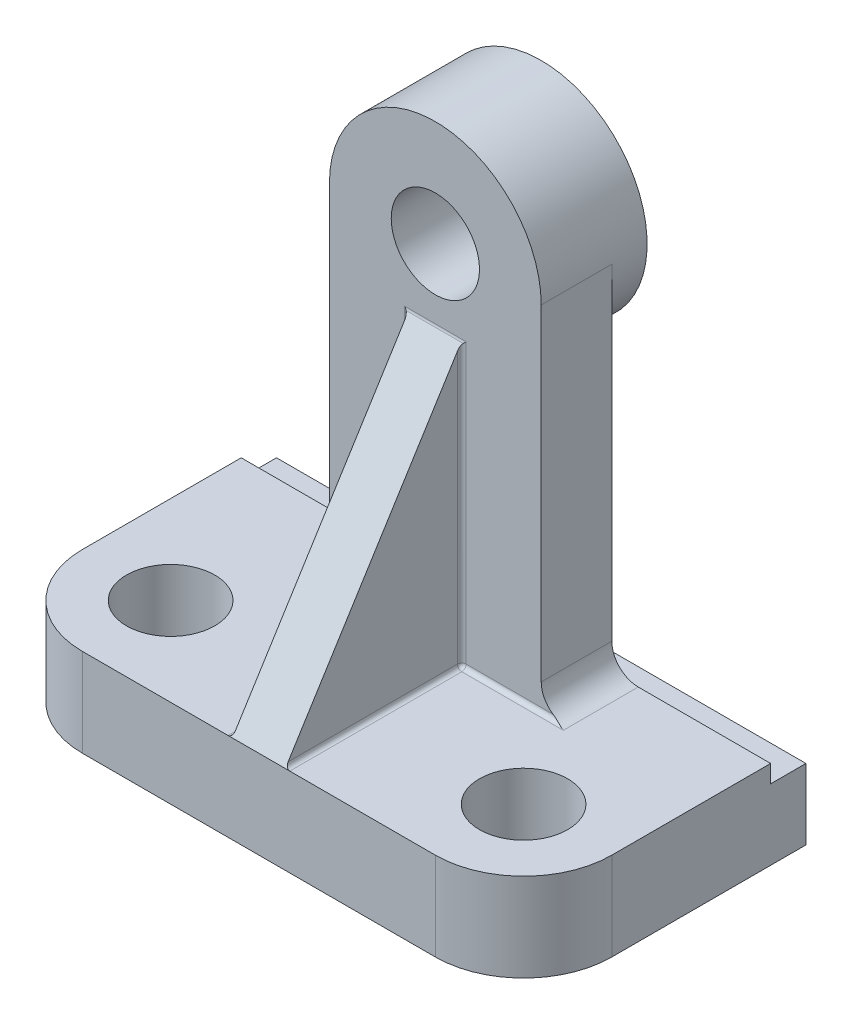
SolidWorks part; units mm, degrees
ref_plane "Front Plane" through (0, 0, 0) normal (0, 0, 1) x (1, 0, 0)
ref_plane "Top Plane" through (0, 0, 0) normal (0, 1, 0) x (1, 0, 0)
ref_plane "Right Plane" through (0, 0, 0) normal (1, 0, 0) x (0, 0, -1)
sketch "Sketch2" plane through (0, 0, 0) normal (0, 1, 0) x (1, 0, 0)
  line L0 (-64.7082, 0) -> (15.2918, 0)
  line L1 (35.2918, 20) -> (35.2918, 64)
  line L4 (35.2918, 20) -> (-131.6865, 20) construction
  line L5 (-84.7082, 20) -> (-84.7082, 64)
  line L6 (-84.7082, 64) -> (35.2918, 64)
  arc A0 (15.2918, 0) -> (35.2918, 20) centre (15.2918, 20) ccw
  arc A2 (-64.7082, 0) -> (-84.7082, 20) centre (-64.7082, 20) cw
  circle A3 centre (-64.7082, 20) radius 10
  circle A4 centre (15.2918, 20) radius 10
  dimension "D1" = 20
  dimension "D2" = 20
  dimension "D5" = 20
  dimension "D6" = 20
  dimension "D3" = 80
  dimension "D4" = 64
extrude "Boss-Extrude1" add sketch "Sketch2" along normal blind 20
sketch "Sketch3" plane through (0, 20, 0) normal (0, 1, 0) x (1, 0, 0)
  line L0 (35.2918, 20) -> (35.2918, 64) construction
  line L1 (-84.7082, 64) -> (35.2918, 64)
  line L2 (-84.7082, 64) -> (-84.7082, 56)
  line L3 (-84.7082, 56) -> (35.2918, 56)
  line L4 (35.2918, 64) -> (35.2918, 56)
  dimension "D1" = 8
extrude "Cut-Extrude1" cut sketch "Sketch3" against normal blind 4
ref_plane "Plane2" through (0, 0, -56) normal (0, 0, -1) x (-1, 0, 0)
sketch "Sketch7" plane through (0, 0, -56) normal (0, 0, -1) x (-1, 0, 0)
  line L0 (24.7082, 20) -> (24.7082, 100) construction
  line L1 (84.7082, 20) -> (-35.2918, 20) construction
  line L7 (24.7082, 20) -> (54.7082, 20)
  line L8 (48.7082, 26) -> (48.7082, 100)
  line L9 (0.7082, 100) -> (0.7082, 26)
  line L10 (-5.2918, 20) -> (24.7082, 20)
  line L11 (-35.2918, 0) -> (84.7082, 0) construction
  circle A1 centre (24.7082, 100) radius 10
  arc A2 (54.7082, 20) -> (48.7082, 26) centre (54.7082, 26) cw
  arc A3 (48.7082, 100) -> (0.7082, 100) centre (24.7082, 100) ccw
  arc A4 (0.7082, 26) -> (-5.2918, 20) centre (-5.2918, 26) cw
  dimension "D1" = 24
  dimension "D3" = 20
  dimension "D4" = 6
  dimension "D5" = 6
  dimension "D2" = 100
extrude "Boss-Extrude2" add sketch "Sketch7" against normal blind 16
sketch "Sketch8" plane through (0, 0, -56) normal (0, 0, -1) x (-1, 0, 0)
  circle A0 centre (24.7082, 100) radius 24
  circle A1 centre (24.7082, 100) radius 10
  dimension "D1" = 48
extrude "Boss-Extrude3" add sketch "Sketch8" along normal blind 8
ref_plane "Plane3" through (-24.7082, 0, 0) normal (-1, 0, 0) x (0, 0, 1)
sketch "Sketch9" plane through (-24.7082, 0, 0) normal (-1, 0, 0) x (0, 0, 1)
  line L1 (-40, 26) -> (-40, 100) construction
  line L3 (0, 20) -> (-20, 20) construction
  line L4 (0, 20) -> (-40, 84)
  line L6 (-56, 20) -> (-20, 20) construction
  point P1 (0, 0)
  point P8 (0, 0)
  dimension "D1" = 64
  dimension "D2" = 40
rib "Rib4" sketch "Sketch9" sketch "Sketch9" thickness 12 extrusion direction parallel to sketch draft on no parameters "D1"=12
fillet "Fillet2" radius 1 7 edges at (-42.7082, 20, -40) (-6.7082, 20, -40) (-30.7082, 20, -20) (-18.7082, 20, -20) (-18.7082, 52, -40) (-30.7082, 52, -40) (-24.7082, 84, -40)
